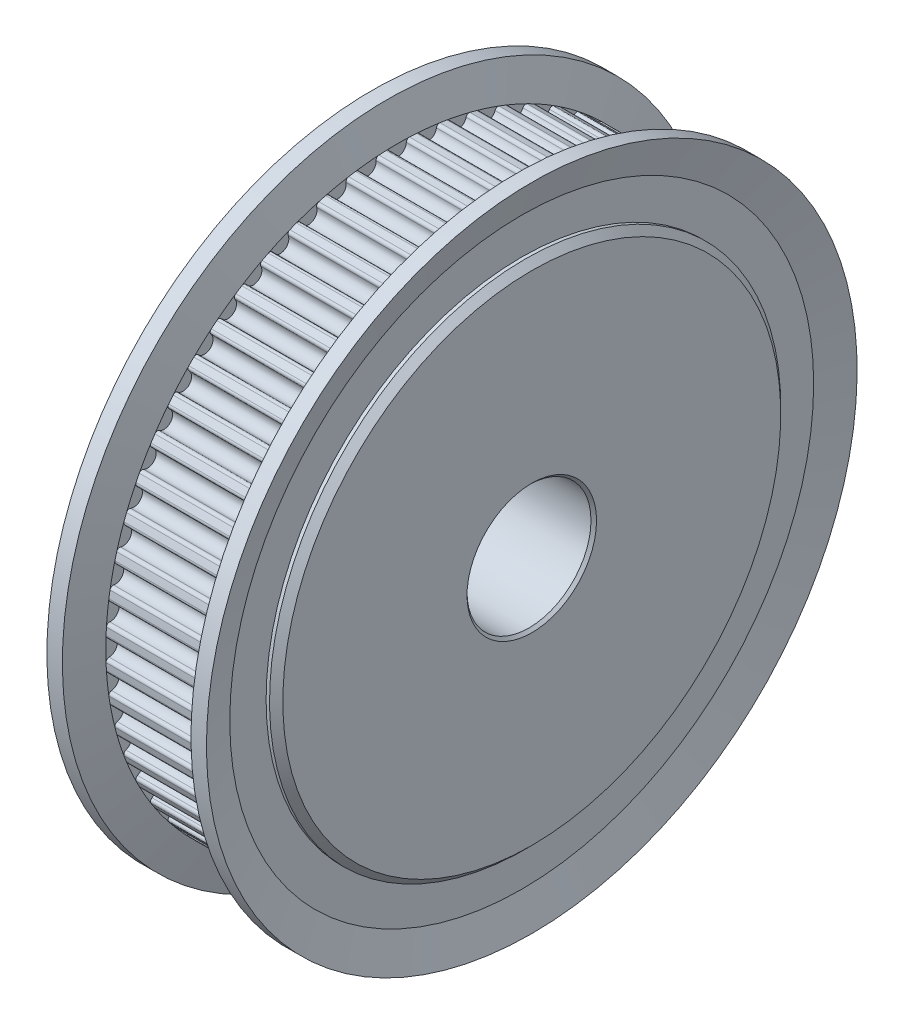
SolidWorks part; units mm, degrees
ref_plane "前视基准面" through (0, 0, 0) normal (0, 0, 1) x (1, 0, 0)
ref_plane "上视基准面" through (0, 0, 0) normal (0, 1, 0) x (1, 0, 0)
ref_plane "右视基准面" through (0, 0, 0) normal (1, 0, 0) x (0, 0, -1)
sketch "草图1" plane through (0, 0, 0) normal (1, 0, 0) x (0, 0, -1)
  line L0 (0, 0) -> (60, 0)
  line L1 (0, 0) -> (0, 19.1) construction
  line L6 (-1.5, 3.7081) -> (1.5, 3.7081)
  line L7 (-1.5, 3.7081) -> (-1.5, 5.4)
  line L8 (-1.5, 5.4) -> (1.5, 5.4)
  line L9 (1.5, 3.7081) -> (1.5, 5.4)
  circle A0 centre (0, 0) radius 19.1
  arc A1 (-0.7579, 18.8298) -> (18.845, 0) centre (0, 0) ccw
  circle A6 centre (0, 0) radius 4
  arc A18 (-0.5499, 18.6339) -> (0.5499, 18.6339) centre (0, 18.645) ccw
  arc A19 (-0.7579, 18.8298) -> (-0.5499, 18.6339) centre (-0.7498, 18.6299) cw
  arc A20 (0.7579, 18.8298) -> (0.5499, 18.6339) centre (0.7498, 18.6299) ccw
  point P8 (0, 18.095)
  point P20 (0, 18.845)
  point P26 (0, 4)
  dimension "D1" = 0.2
  dimension "PD" = 38.2
  dimension "OD" = 37.69
  dimension "H" = 8
  dimension "D2" = 0.75
  dimension "D3" = 0.2
  dimension "齿数" = 60
  dimension "t" = 1.4
  dimension "b" = 3
sketch "草图2" plane through (0, 0, 0) normal (0, 0, 1) x (1, 0, 0)
  line L0 (0, 0) -> (10.3, 0) construction
  line L1 (0, 0) -> (0, 16.5)
  line L2 (0, 16.5) -> (1.65, 16.5)
  line L3 (1.65, 16.5) -> (1.65, 18.845)
  line L4 (1.65, 18.845) -> (8.65, 18.845)
  line L5 (8.65, 18.845) -> (8.65, 16.5)
  line L6 (8.65, 16.5) -> (10.3, 16.5)
  line L7 (10.3, 16.5) -> (10.3, 0)
  line L8 (0, 0) -> (0, 19.1) construction
  line L9 (0.65, 16.5) -> (0.65, 18.845)
  line L10 (0.65, 18.845) -> (0, 21)
  line L11 (0, 21) -> (1, 21)
  line L12 (1, 21) -> (1.65, 18.845)
  line L13 (1.65, 18.845) -> (1.65, 16.5)
  line L14 (5.15, 18.845) -> (5.15, 0) construction
  line L15 (7.15, 18.845) -> (7.15, 0)
  line L17 (10.3, 0.5) -> (7.3, 0.5)
  line L18 (0, 0.5) -> (3, 0.5)
  point P27 (3, 0.5)
  dimension "A" = 7
  dimension "W" = 10.3
  dimension "E" = 33
  dimension "D2" = 1.65
  dimension "D3" = 1
  dimension "F" = 42
  dimension "M" = 4
  dimension "S" = 3
  dimension "R" = 1
  dimension "T" = 3
  dimension "Q" = 1
  dimension "J" = 3
  dimension "Z" = 1
sketch "草图3" plane through (0, 0, 0) normal (0, 0, 1) x (1, 0, 0)
  line L0 (0, 0) -> (0, 16.07)
  line L1 (0.43, 16.5) -> (1.65, 16.5)
  line L2 (1.65, 16.5) -> (1.65, 18.845)
  line L3 (1.65, 18.845) -> (8.65, 18.845)
  line L4 (8.65, 18.845) -> (8.65, 16.5)
  line L5 (8.65, 16.5) -> (9.87, 16.5)
  line L6 (10.3, 16.07) -> (10.3, 0)
  line L7 (10.3, 0) -> (0, 0)
  line L8 (0, 16.07) -> (0.43, 16.5)
  line L9 (9.87, 16.5) -> (10.3, 16.07)
  point P1 (0, 16.5)
  point P13 (10.3, 16.5)
  dimension "D1" = 0.43
  dimension "D2" = 45
  dimension "D4" = 45
revolve "旋转1" add sketch "草图3" angle 360 about L7
sketch "草图4" plane through (0, 0, 0) normal (1, 0, 0) x (0, 0, -1)
  arc A0 (0.7579, 18.8298) -> (-0.7579, 18.8298) centre (0, 0) ccw
  arc A1 (-0.7579, 18.8298) -> (18.845, 0) centre (0, 0) ccw construction
  arc A2 (-0.5499, 18.6339) -> (-0.7579, 18.8298) centre (-0.7498, 18.6299) ccw construction
  arc A3 (-0.5499, 18.6339) -> (0.5499, 18.6339) centre (0, 18.645) ccw construction
  arc A4 (0.7579, 18.8298) -> (0.5499, 18.6339) centre (0.7498, 18.6299) ccw construction
  arc A5 (-0.5499, 18.6339) -> (-0.7579, 18.8298) centre (-0.7498, 18.6299) ccw
  arc A8 (-0.5499, 18.6339) -> (0.5499, 18.6339) centre (0, 18.645) ccw
  arc A12 (0.7579, 18.8298) -> (0.5499, 18.6339) centre (0.7498, 18.6299) ccw
extrude "切除-拉伸1" cut sketch "草图4" along normal up to vertex (8.65 mm away) from vertex at 1.65 starting at point (1.65, 18.845, 0)
pattern_circular "阵列(圆周)1" count 60 over 360 about axis through (0, 0, 0) along (1, 0, 0) of "切除-拉伸1"
sketch "草图5" plane through (0, 0, 0) normal (0, 0, 1) x (1, 0, 0)
  line L0 (1, 21) -> (1.65, 18.845) construction
  line L1 (0, 21) -> (1, 21) construction
  line L2 (0.65, 18.845) -> (0, 21) construction
  line L3 (0.65, 16.5) -> (0.65, 18.845) construction
  line L4 (1.65, 16.5) -> (1.65, 18.845) construction
  line L5 (1, 21) -> (1.65, 18.845)
  line L6 (0, 21) -> (1, 21)
  line L7 (0.65, 18.845) -> (0, 21)
  line L8 (0.65, 16.5) -> (0.65, 18.845)
  line L9 (1.65, 16.5) -> (1.65, 18.845)
  line L10 (0.65, 16.5) -> (1.65, 16.5)
  line L11 (0, 0) -> (10.3, 0) construction
  line L12 (5.15, 18.845) -> (5.15, 0) construction
  line L13 (9.65, 16.5) -> (8.65, 16.5)
  line L14 (9.65, 16.5) -> (9.65, 18.845)
  line L15 (9.65, 18.845) -> (10.3, 21)
  line L16 (10.3, 21) -> (9.3, 21)
  line L17 (9.3, 21) -> (8.65, 18.845)
  line L18 (8.65, 16.5) -> (8.65, 18.845)
revolve "旋转2" add sketch "草图5" angle 360 about L11
sketch "草图6" plane through (0, 0, 0) normal (1, 0, 0) x (0, 0, -1)
  circle A0 centre (0, 0) radius 4 construction
  circle A1 centre (0, 0) radius 4
extrude "切除-拉伸2" cut sketch "草图6" along normal through all
chamfer "倒角1" distance 0.18 angle 45 2 edges at (0, 0, -4) (10.3, 0, -4)
